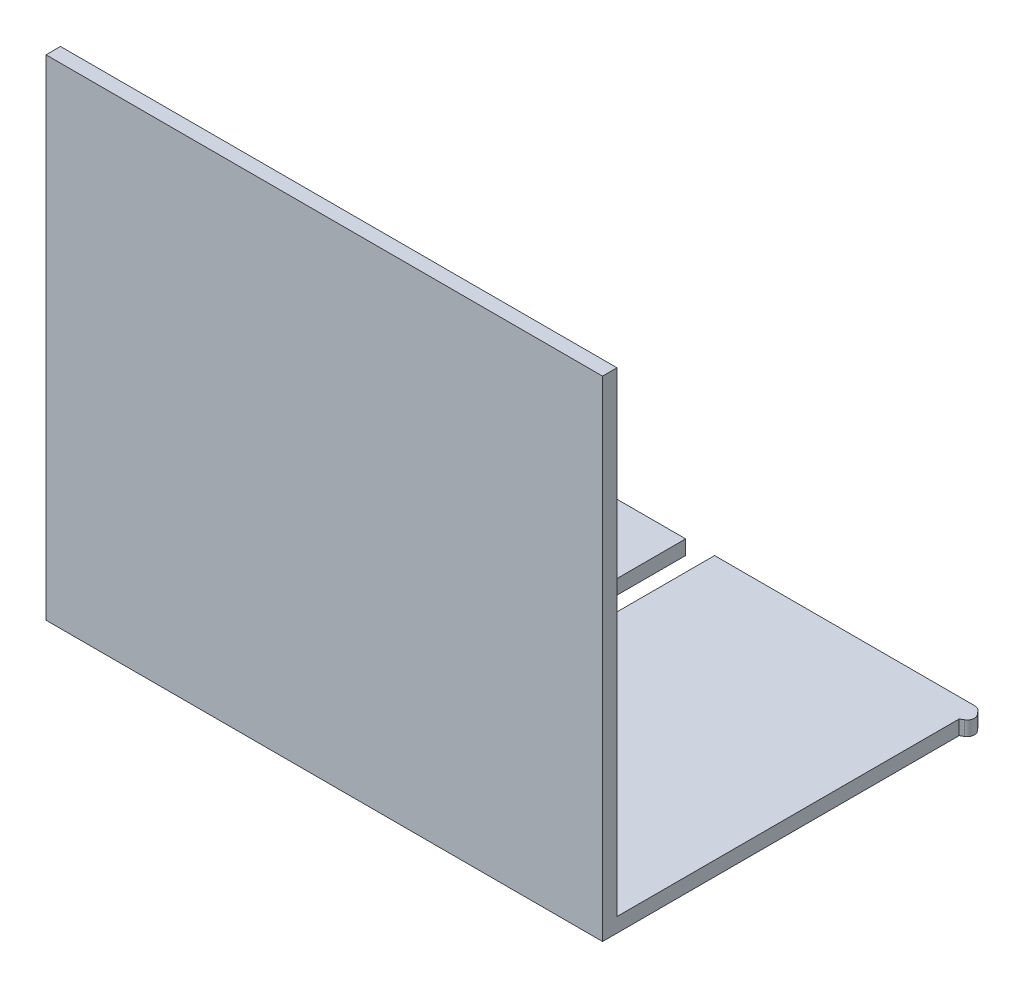
SolidWorks part; units mm, degrees
ref_plane "Front Plane" through (0, 0, 0) normal (0, 0, 1) x (1, 0, 0)
ref_plane "Top Plane" through (0, 0, 0) normal (0, 1, 0) x (1, 0, 0)
ref_plane "Right Plane" through (0, 0, 0) normal (1, 0, 0) x (0, 0, -1)
sketch "Sketch1" plane through (0, 0, 0) normal (0, 1, 0) x (1, 0, 0)
  line L1 (-38.5, 25) -> (38.5, 25)
  line L2 (-38.5, 25) -> (-38.5, -25)
  line L3 (-38.5, -25) -> (38.5, -25)
  line L4 (38.5, 25) -> (38.5, -25)
  line L5 (-38.5, 25) -> (38.5, -25) construction
  line L6 (-38.5, -25) -> (38.5, 25) construction
  point P0 (0, 0)
  dimension "D1" = 77
  dimension "D2" = 50
extrude "Boss-Extrude1" add sketch "Sketch1" along normal blind 2
sketch "Sketch2" plane through (0, 0, 0) normal (0, -1, 0) x (1, 0, 0)
  line L0 (-38.5, -25) -> (-38.5, 25) construction
  line L1 (38.5, 25) -> (-38.5, 25)
  line L2 (38.5, 25) -> (38.5, 27)
  line L3 (38.5, 27) -> (-38.5, 27)
  line L4 (-38.5, 25) -> (-38.5, 27)
  point P5 (-38.5, 25)
  dimension "D1" = 2
extrude "Boss-Extrude2" add sketch "Sketch2" against normal blind 67.75
sketch "Sketch3" plane through (0, 2, 0) normal (0, 1, 0) x (1, 0, 0)
  line L0 (2, 25) -> (2, -15)
  line L1 (38.5, 25) -> (-38.5, 25) construction
  line L2 (-2, -15) -> (-2, 25)
  line L3 (-2, 25) -> (2, 25)
  line L4 (0, -15) -> (0, 0) construction
  arc A0 (2, -15) -> (-2, -15) centre (0, -15) cw
  point P6 (8.1134, -10.4071)
  point P10 (2.7856, -9.4177)
  dimension "D2" = 2
  dimension "D1" = 40
extrude "Cut-Extrude1" cut sketch "Sketch3" against normal through all
sketch "Sketch4" plane through (0, 2, 0) normal (0, 1, 0) x (1, 0, 0)
  line L0 (-38.5, 25) -> (-40, 23.2124)
  line L1 (-40, 23.2124) -> (-38.5, 22.3463)
  line L2 (-38.5, 25) -> (-38.5, -25) construction
  line L3 (-38.5, 22.3463) -> (-38.5, 25)
  line L4 (-40, 23.2124) -> (-38.5, 23.2124) construction
  line L5 (0, 0) -> (0, -25) construction
  line L6 (-38.5, -25) -> (38.5, -25) construction
  line L7 (40, 23.2124) -> (38.5, 22.3463)
  line L8 (38.5, 25) -> (40, 23.2124)
  line L9 (38.5, 22.3463) -> (38.5, 25)
  dimension "D1" = 1.5
  dimension "D2" = 60
  dimension "D3" = 40
extrude "Boss-Extrude3" add sketch "Sketch4" against normal up to surface (2 mm away) up to face at (0, 0, -1.75)
fillet "Fillet1" radius 1 4 edges at (40, 1, -23.2124) (-40, 1, -23.2124) (38.5, 1, -25) (-38.5, 1, -25)
